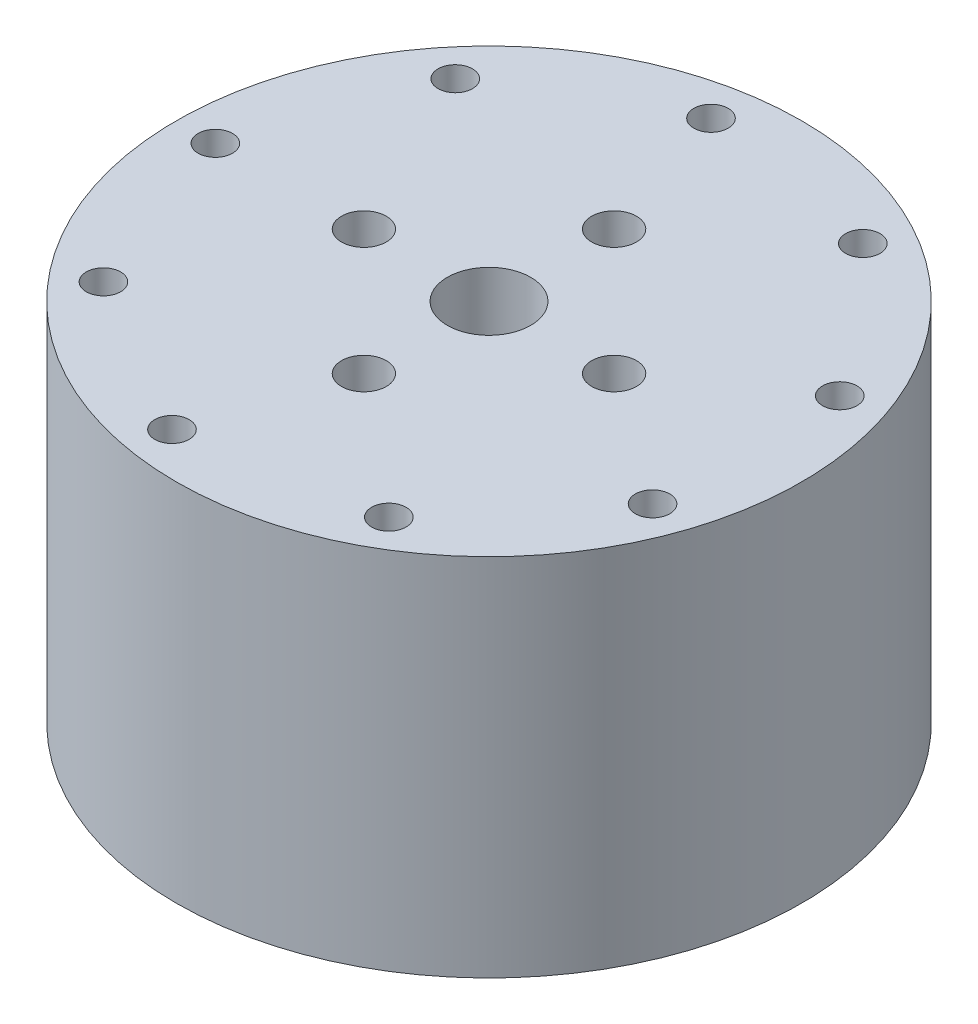
SolidWorks part; units mm, degrees
ref_plane "前视基准面" through (0, 0, 0) normal (0, 0, 1) x (1, 0, 0)
ref_plane "上视基准面" through (0, 0, 0) normal (0, 1, 0) x (1, 0, 0)
ref_plane "右视基准面" through (0, 0, 0) normal (1, 0, 0) x (0, 0, -1)
sketch "草图1" plane through (0, 0, 0) normal (0, 1, 0) x (1, 0, 0)
  circle A0 centre (0, 0) radius 30
extrude "凸台-拉伸1" add sketch "草图1" along normal blind 35
sketch3d "3D草图1"
  line L0 (-71.4046, 17.5, 0) -> (71.4046, 17.5, 0)
  line L1 (0, 17.5, 0) -> (-50, 17.5, 0)
  point P0 (0, 17.5, 0)
  point P4 (0, 17.5, 0)
  point P5 (0, 17.5, 0)
sketch "草图2" plane through (0, 0, 0) normal (0, -1, 0) x (1, 0, 0)
  circle A1 centre (-26.25, 0) radius 1.65
  circle A2 centre (-20.1087, 16.8732) radius 1.65
  circle A3 centre (-4.5583, 25.8512) radius 1.65
  circle A4 centre (13.125, 22.7332) radius 1.65
  circle A5 centre (24.6669, 8.978) radius 1.65
  circle A6 centre (24.6669, -8.978) radius 1.65
  circle A7 centre (13.125, -22.7332) radius 1.65
  circle A8 centre (-4.5583, -25.8512) radius 1.65
  circle A9 centre (-20.1087, -16.8732) radius 1.65
  point P24 (0, 0)
  dimension "D1" = 9
extrude "切除-拉伸1" cut sketch "草图2" against normal through all
sketch "草图4" plane through (0, 0, 0) normal (0, -1, 0) x (1, 0, 0)
  circle A0 centre (0, 0) radius 20
extrude "切除-拉伸3" cut sketch "草图4" against normal blind 10
sketch "草图5" plane through (0, 10, 0) normal (0, -1, 0) x (1, 0, 0)
  circle A0 centre (0, 0) radius 4
extrude "切除-拉伸4" cut sketch "草图5" against normal through all
sketch "草图6" plane through (0, 10, 0) normal (0, -1, 0) x (1, 0, 0)
  circle A9 centre (0, 12) radius 2.15
  circle A10 centre (12, 0) radius 2.15
  circle A11 centre (0, -12) radius 2.15
  circle A12 centre (-12, 0) radius 2.15
  point P11 (0, 0)
  point P12 (0, 0)
  point P18 (0, 0)
  dimension "D1" = 4
extrude "切除-拉伸5" cut sketch "草图6" against normal through all
